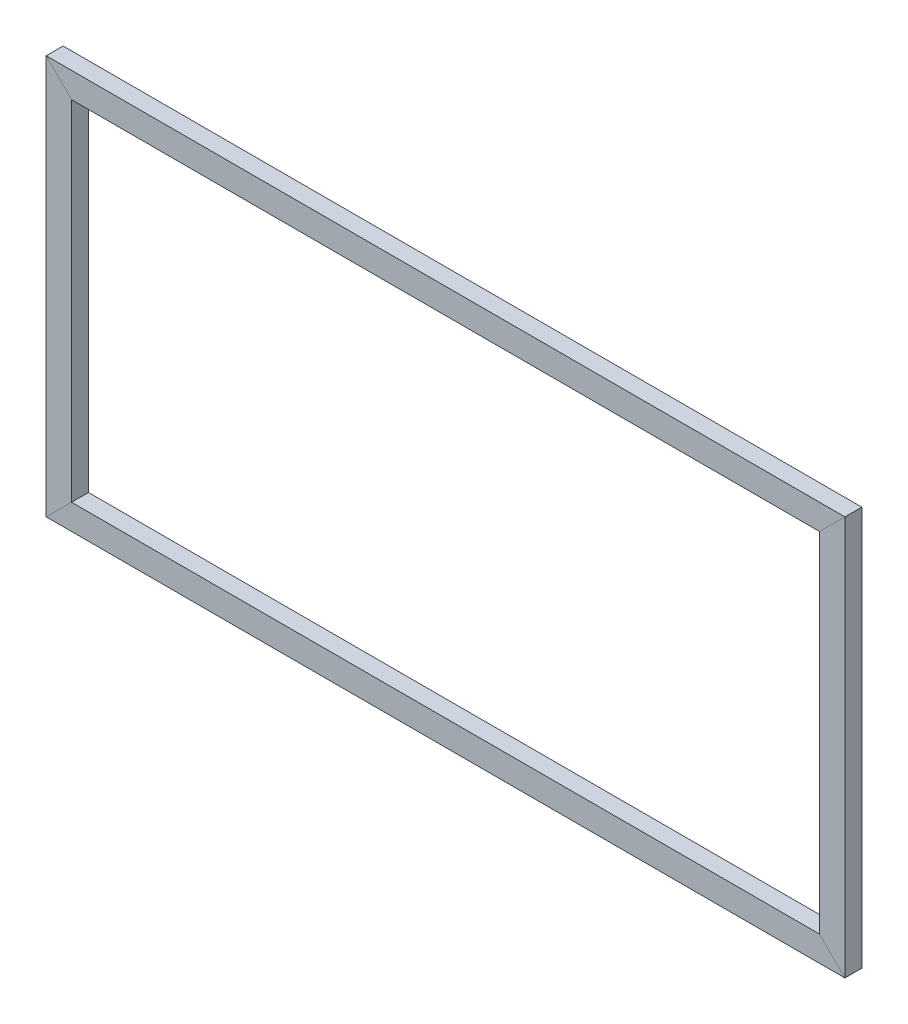
SolidWorks part; units mm, degrees
other "Carpeta de soldadura"
ref_plane "Alzado" through (0, 0, 0) normal (0, 0, 1) x (1, 0, 0)
ref_plane "Planta" through (0, 0, 0) normal (0, 1, 0) x (1, 0, 0)
ref_plane "Vista lateral" through (0, 0, 0) normal (1, 0, 0) x (0, 0, -1)
sketch "Croquis1" plane through (0, 0, 0) normal (0, 0, 1) x (1, 0, 0)
  line L1 (290.475, 140.475) -> (-290.475, 140.475)
  line L2 (290.475, 140.475) -> (290.475, -140.475)
  line L3 (290.475, -140.475) -> (-290.475, -140.475)
  line L4 (-290.475, 140.475) -> (-290.475, -140.475)
  line L5 (290.475, 140.475) -> (-290.475, -140.475) construction
  line L6 (290.475, -140.475) -> (-290.475, 140.475) construction
  point P0 (0, 0)
  dimension "D1" = 280.95
  dimension "D2" = 580.95
other "Al solid profiles 0.75 X 0.5(1)"
ref_plane "Plano1" through (290.475, -140.475, 0) normal (-1, 0, 0) x (0, -1, 0)
sketch "Croquis18" plane through (290.475, -140.475, 0) normal (-1, 0, 0) x (0, -1, 0)
  line L1 (9.525, 6.35) -> (-9.525, 6.35)
  line L2 (9.525, 6.35) -> (9.525, -6.35)
  line L3 (9.525, -6.35) -> (-9.525, -6.35)
  line L4 (-9.525, 6.35) -> (-9.525, -6.35)
  line L5 (9.525, 6.35) -> (-9.525, -6.35) construction
  line L6 (9.525, -6.35) -> (-9.525, 6.35) construction
  point P0 (0, 0)
  point P5 (0, 0)
  dimension "D1" = 12.7
  dimension "D2" = 19.05
